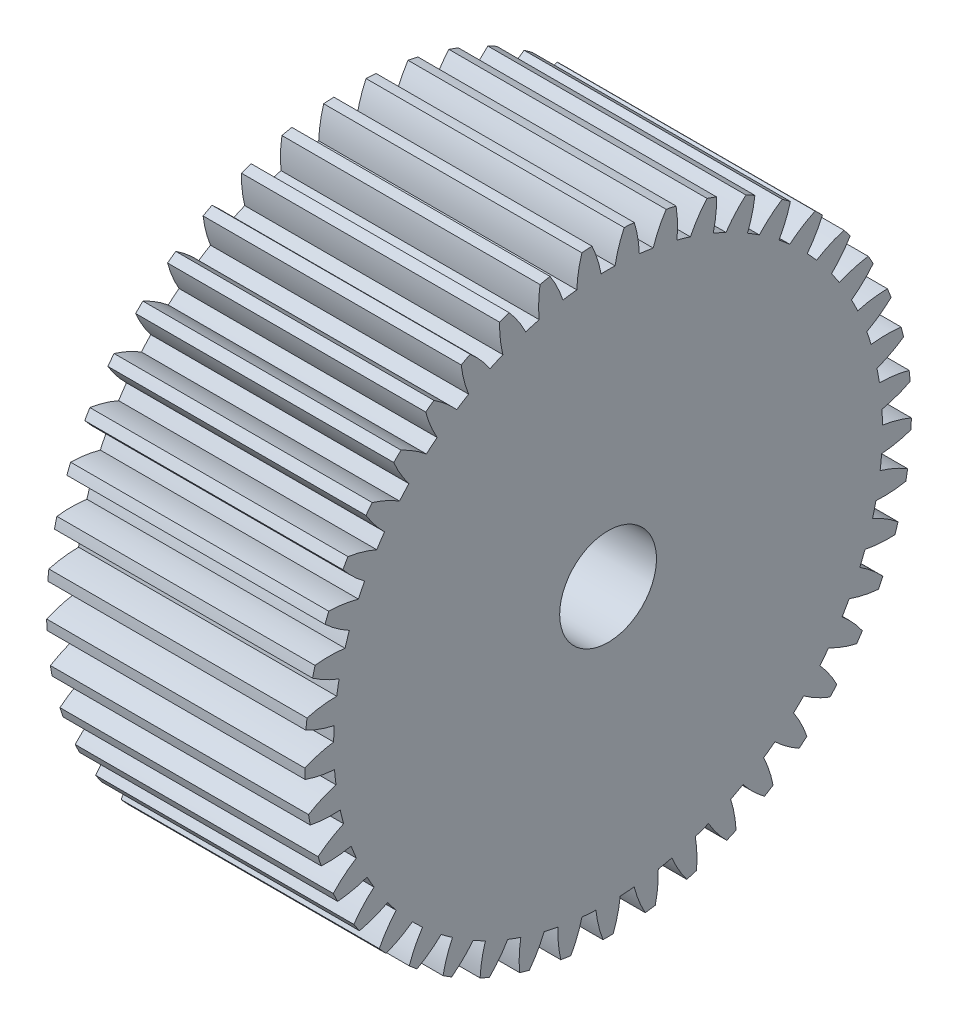
SolidWorks part; units mm, degrees
ref_plane "Plane1" through (0, 0, 0) normal (0, 0, 1) x (1, 0, 0)
ref_plane "Plane2" through (0, 0, 0) normal (0, 1, 0) x (1, 0, 0)
ref_plane "Plane3" through (0, 0, 0) normal (1, 0, 0) x (0, 0, -1)
sketch "HoldingSke" plane through (0, 0, 0) normal (0, 1, 0) x (1, 0, 0)
  line L0 (0, 0) -> (359.2102, -359.2102)
  line L1 (-15, 0) -> (100, 0) construction
  line L2 (0, 0) -> (-2.1039, 2.3779)
  line L3 (0, 0) -> (-11.863, 4.5341)
  line L4 (0, 0) -> (6.1066, 6.1066)
  line L5 (0, 0) -> (-47.5972, -17.7524)
  line L6 (0, 0) -> (-21.0557, -14.2063)
  line L7 (-2.1039, 2.3779) -> (8.8308, 51.9871)
  line L8 (-76.2, 54.61) -> (-65.4837, 54.61)
  line L9 (-67.7845, 28.3722) -> (-49.3413, 33.142)
  line L10 (-76.2, 71.12) -> (104.1128, 71.12)
  line L11 (0, 0) -> (-25.4, 0)
  line L12 (-76.2, 101.6) -> (-76.1492, 101.6)
  line L13 (24.9733, 27.94) -> (52.9518, 28.4284)
  line L14 (24.9733, 27.94) -> (25.0241, 27.9398)
  line L15 (24.9733, 27.94) -> (100.4021, 29.52)
  circle A0 centre (0, 0) radius 4.7625
  circle A1 centre (0, 0) radius 27.0002
  circle A2 centre (0, 0) radius 38.1
  circle A3 centre (0, 0) radius 4.7625
  dimension "Hub_dia" = 76.2
  dimension "Bore" = 9.525
  dimension "MBD" = 9.525
  dimension "Pitch" = 508
  dimension "Overall_len" = 50.8
  dimension "OAL" = 50.8001
  dimension "T_dim" = 10.7163
  dimension "Ap" = 14.5
  dimension "H" = 19.05
  dimension "Pitch_radius" = 180.3128
  dimension "Backlash" = 0.0508
  dimension "Addendum_fac" = 1
  dimension "Dedendum_fac" = 1.2
  dimension "Clearance_fac" = 0.2
  dimension "Dedendum_add" = 0.0508
sketch "BasProSke" plane through (0, 0, 0) normal (0, 1, 0) x (1, 0, 0)
  line L0 (-10, 0) -> (60, 0) construction
  line L1 (0, 0) -> (0, 29.845)
  line L2 (0, 0) -> (25.4, 0)
  line L3 (25.4, 0) -> (25.4, 29.845)
  line L4 (25.4, 29.845) -> (0, 29.845)
revolve "Base-Revolve" add sketch "BasProSke" angle 360 about L0
sketch "TooCutSke" plane through (0, 0, 0) normal (1, 0, 0) x (0, 0, -1)
  line L1 (0, 0) -> (0, 107) construction
  line L2 (0, 0) -> (-1.0861, 28.5544) construction
  line L3 (0, 0) -> (-3.9846, 56.982) construction
  line L4 (-1.0861, 28.5544) -> (-1.9923, 28.491) construction
  arc A0 (0.6879, 26.9914) -> (-0.6879, 26.9914) centre (0, 0) ccw
  arc A1 (1.595, 29.8278) -> (-1.595, 29.8278) centre (0, 0) ccw
  circle A2 centre (0, 0) radius 28.575 construction
  circle A3 centre (0, 0) radius 27.6648 construction
  arc A4 (-0.6879, 26.9914) -> (-1.595, 29.8278) centre (-11.9355, 24.9577) ccw
  arc A5 (1.595, 29.8278) -> (0.6879, 26.9914) centre (11.9355, 24.9577) ccw
  dimension "Half_CT" = 0.9084
extrude "ToothCut" cut sketch "TooCutSke" along normal through all
fillet "Breaks" [suppressed] radius 0.0254
fillet "RootFillets" [suppressed] radius 0.3048
pattern_circular "TeethCuts" count 45 every 8 about axis through (-10, 0, 0) along (1, 0, 0) of "ToothCut", "RootFillets", "Breaks"
sketch "HubNeaOneSke" plane through (0, 0, 0) normal (-1, 0, 0) x (0, 0, 1)
  circle A0 centre (0, 0) radius 27.0002
extrude "HubNearOne" [suppressed] add sketch "HubNeaOneSke" along normal blind 25.4001
sketch "HubNeaBotSke" plane through (0, 0, 0) normal (-1, 0, 0) x (0, 0, 1)
  circle A0 centre (0, 0) radius 27.0002
extrude "HubNearBoth" [suppressed] add sketch "HubNeaBotSke" along normal blind 12.7
ref_plane "FarPln" through (25.4, 0, 0) normal (1, 0, 0) x (0, 0, -1)
sketch "HubFarSke" plane through (25.4, 0, 0) normal (1, 0, 0) x (0, 0, -1)
  circle A0 centre (0, 0) radius 27.0002
extrude "HubFar" [suppressed] add sketch "HubFarSke" along normal blind 12.7
sketch "BorSke" plane through (0, 0, 0) normal (1, 0, 0) x (0, 0, -1)
  circle A0 centre (0, 0) radius 4.7625
  dimension "Diameter" = 9.525
extrude "Bore" cut sketch "BorSke" along normal mid plane 101.6001
sketch "KeySke" plane through (0, 0, 0) normal (1, 0, 0) x (0, 0, -1)
  line L0 (-1.1913, 0) -> (-1.1913, 5.9538)
  line L1 (-1.1913, 5.9538) -> (1.1913, 5.9538)
  line L2 (1.1913, 5.9538) -> (1.1913, 0)
  line L3 (0, 0) -> (0, 34) construction
  line L4 (-1.1913, 0) -> (1.1913, 0)
  dimension "Offset" = 5.9538
  dimension "Width" = 2.3825
extrude "Keyway" [suppressed] cut sketch "KeySke" along normal mid plane 101.6001
pattern_circular "Keyway2" [suppressed] count 2 every 90 about axis through (-10, 0, 0) along (1, 0, 0)
equation "' \"Pitch@HoldingSke\" = 4"
equation "' \"Num_teeth@HoldingSke\" = 12"
equation "' \"Ap@HoldingSke\" =  20"
equation "' \"Ap@HoldingSke\" = 20"
equation "' \"Width@HoldingSke\" = 0.5"
equation "' \"Hub_dia@HoldingSke\"= 1"
equation "' \"Hub_dia@HoldingSke\" = 1"
equation "' \"Overall_len@HoldingSke\" = 1.0"
equation "' \"Bore@HoldingSke\" = 0.75"
equation "' \"T_dim@HoldingSke\" = 0.85"
equation "' \"Width@KeySke\" = 0.25"
equation "' \"Show_teeth@HoldingSke\" = 13"
equation "' \"Backlash@HoldingSke\" = 0.009"
equation "' \"Addendum_fac@HoldingSke\" = 1.0"
equation "' \"Dedendum_fac@HoldingSke\" = 1.25"
equation "' \"Dedendum_add@HoldingSke\" = 0.00005"
equation "' \"Clearance_fac@HoldingSke\" = 0.25"
equation "' \"Pitch@HoldingSke\" = 0.5"
equation "' \"Num_teeth@HoldingSke\" = 23"
equation "' \"Show_teeth@HoldingSke\" = 23"
equation "' \"Backlash@HoldingSke\" = 0.0375"
equation "\"Overcut_dia@TooCutSke\" = (\"Num_teeth@HoldingSke\" + 2 * \"Addendum_fac@HoldingSke\") / \"Pitch@HoldingSke\" + 0.002"
equation "\"Pitch_dia@TooCutSke\" = \"Num_teeth@HoldingSke\" / \"Pitch@HoldingSke\""
equation "\"Base_dia@TooCutSke\" = \"Num_teeth@HoldingSke\" / \"Pitch@HoldingSke\" * cos((\"Ap@HoldingSke\"  * 3.14159265 / 180))"
equation "\"Root_dia@TooCutSke\" = (\"Num_teeth@HoldingSke\" + 2) / \"Pitch@HoldingSke\" - 2 * (\"Addendum_fac@HoldingSke\" + \"Dedendum_fac@HoldingSke\") / \"Pitch@HoldingSke\" - \"Dedendum_add@HoldingSke\" * 2"
equation "\"Half_ang@TooCutSke\" = 180 / \"Num_teeth@HoldingSke\""
equation "\"Half_CT@TooCutSke\" = \"Num_teeth@HoldingSke\" / \"Pitch@HoldingSke\" * sin((3.14159265 / 2 / \"Num_teeth@HoldingSke\")) / 2 - 7 * \"Backlash@HoldingSke\" / 4"
equation "\"Flank_rad@TooCutSke\" = \"Num_teeth@HoldingSke\" / \"Pitch@HoldingSke\" / 5"
equation "\"Radius@RootFillets\" = \"Clearance_fac@HoldingSke\" / \"Pitch@HoldingSke\" + \"Dedendum_add@HoldingSke\""
equation "\"Break_rad@Breaks\" = 0.02 / \"Pitch@HoldingSke\""
equation "\"Thickness@HoldingSke\" = \"Width@HoldingSke\""
equation "\"OAL@HoldingSke\" = \"Thickness@HoldingSke\""
equation "\"MHD@HoldingSke\" = (\"Num_teeth@HoldingSke\" + 2) / \"Pitch@HoldingSke\" - 2 * (\"Addendum_fac@HoldingSke\" + \"Dedendum_fac@HoldingSke\")  / \"Pitch@HoldingSke\" - \"Dedendum_add@HoldingSke\" * 2"
equation "\"MBD@HoldingSke\" = (\"Num_teeth@HoldingSke\" + 2) / \"Pitch@HoldingSke\" - 2 * (\"Addendum_fac@HoldingSke\" + \"Dedendum_fac@HoldingSke\")  / \"Pitch@HoldingSke\" - \"Dedendum_add@HoldingSke\" * 2 - 0.002"
equation "\"MHD@HoldingSke\" = ((sgn( \"MHD@HoldingSke\" - \"Hub_dia@HoldingSke\" )-1)*( \"MHD@HoldingSke\" - \"Hub_dia@HoldingSke\" ))/-2+ \"Hub_dia@HoldingSke\""
equation "\"MBD@HoldingSke\" = ((sgn( \"MBD@HoldingSke\" - \"Bore@HoldingSke\" )-1)*( \"MBD@HoldingSke\" - \"Bore@HoldingSke\" ))/-2+ \"Bore@HoldingSke\""
equation "\"OAL@HoldingSke\" = ((sgn( \"OAL@HoldingSke\" - \"Overall_len@HoldingSke\" )+1)*( \"OAL@HoldingSke\" - \"Overall_len@HoldingSke\" ))/2 + \"Overall_len@HoldingSke\" + 0.000002"
equation "\"Num_teeth@TeethCuts\" = int( \"Show_teeth@HoldingSke\" ) + 1"
equation "\"Num_teeth@TeethCuts\" = ((sgn( \"Num_teeth@TeethCuts\" - \"Num_teeth@HoldingSke\" )-1)*( \"Num_teeth@TeethCuts\" - \"Num_teeth@HoldingSke\" ))/-2+ \"Num_teeth@HoldingSke\""
equation "\"Num_teeth@TeethCuts\" = ((sgn( \"Num_teeth@TeethCuts\" - 2.0)+1)*( \"Num_teeth@TeethCuts\" - 2.0))/2 +2.0"
equation "\"Angle@TeethCuts\" = 360.0 / \"Num_teeth@HoldingSke\""
equation "\"Diameter@BasProSke\" = (\"Num_teeth@HoldingSke\" + 2 * \"Addendum_fac@HoldingSke\") / \"Pitch@HoldingSke\""
equation "\"Thickness@BasProSke\"  = \"Thickness@HoldingSke\""
equation "' \"Fillet_rad@BasProSke\" =  \"Thickness@HoldingSke\" * 0.05"
equation "' \"Fillet_rad@BasProSke\" = \"Thickness@HoldingSke\" * 0.05"
equation "\"MHD@HoldingSke\" = ((sgn( \"MHD@HoldingSke\" - \"Root_dia@TooCutSke\" )-1)*( \"MHD@HoldingSke\" - \"Root_dia@TooCutSke\" ))/-2+ \"Root_dia@TooCutSke\""
equation "\"Diameter@HubNeaOneSke\" = \"MHD@HoldingSke\""
equation "\"Length@HubNearOne\" = \"OAL@HoldingSke\" - \"Thickness@BasProSke\""
equation "\"Diameter@HubNeaBotSke\" = \"MHD@HoldingSke\""
equation "\"Length@HubNearBoth\" = ( \"OAL@HoldingSke\" - \"Thickness@BasProSke\" ) / 2.0"
equation "\"Thickness@FarPln\" = \"Thickness@BasProSke\""
equation "\"Diameter@HubFarSke\" = \"MHD@HoldingSke\""
equation "\"Length@HubFar\" = ( \"OAL@HoldingSke\" - \"Thickness@BasProSke\" ) / 2.0"
equation "\"Diameter@BorSke\" = \"MBD@HoldingSke\""
equation "\"D1@Bore\" = \"OAL@HoldingSke\" * 2.0"
equation "\"D1@Keyway\" = \"OAL@HoldingSke\" * 2.0"
equation "\"Offset@KeySke\" = \"T_dim@HoldingSke\" - \"MBD@HoldingSke\" / 2.0"
